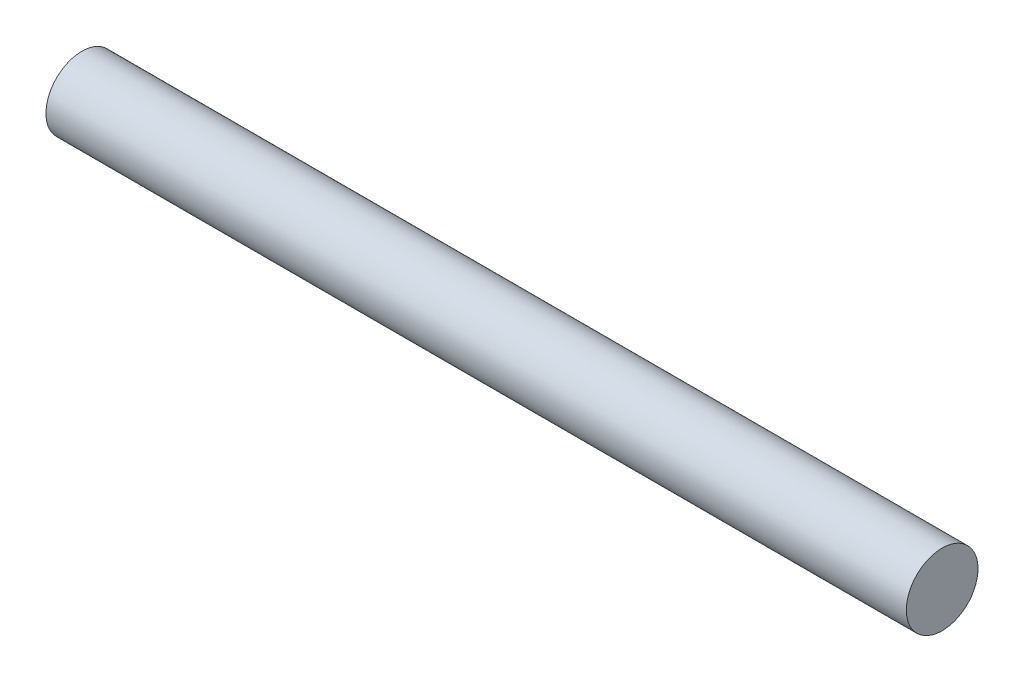
SolidWorks part; units mm, degrees
ref_plane "Front Plane" through (0, 0, 0) normal (0, 0, 1) x (1, 0, 0)
ref_plane "Top Plane" through (0, 0, 0) normal (0, 1, 0) x (1, 0, 0)
ref_plane "Right Plane" through (0, 0, 0) normal (1, 0, 0) x (0, 0, -1)
sketch "Sketch1" plane through (0, 0, 0) normal (1, 0, 0) x (0, 0, -1)
  circle A0 centre (0, 0) radius 25
  dimension "D1" = 50
extrude "Boss-Extrude1" add sketch "Sketch1" along normal mid plane 600
